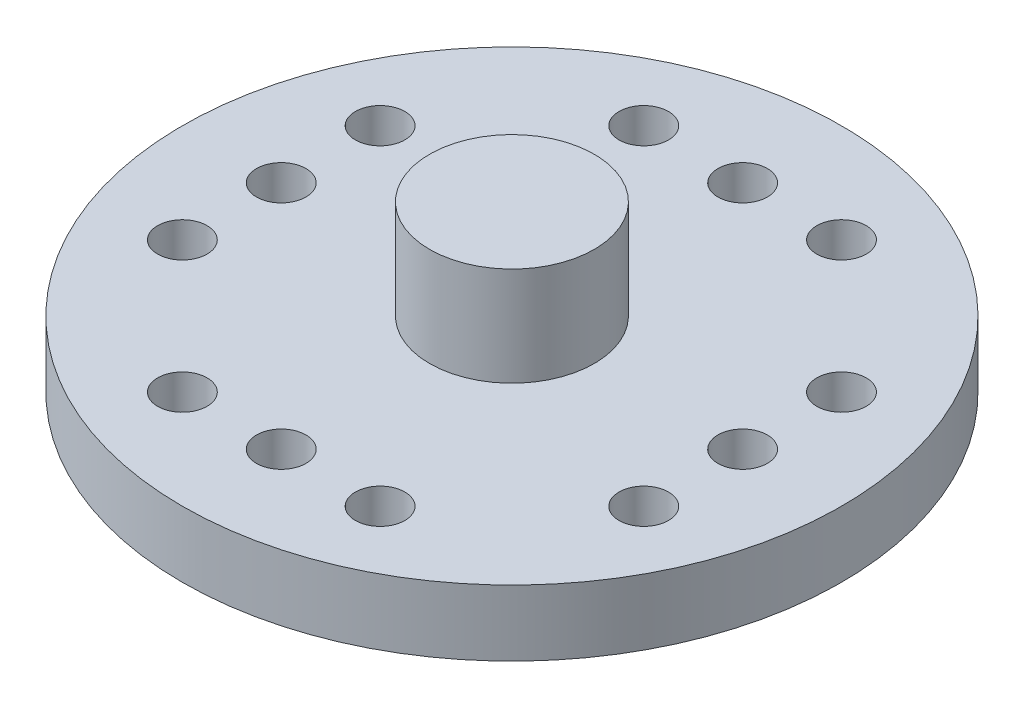
SolidWorks part; units mm, degrees
ref_plane "前视基准面" through (0, 0, 0) normal (0, 0, 1) x (1, 0, 0)
ref_plane "上视基准面" through (0, 0, 0) normal (0, 1, 0) x (1, 0, 0)
ref_plane "右视基准面" through (0, 0, 0) normal (1, 0, 0) x (0, 0, -1)
sketch "草图1" plane through (0, 0, 0) normal (0, 1, 0) x (1, 0, 0)
  circle A0 centre (0, 0) radius 10
  dimension "D1" = 20
extrude "凸台-拉伸1" add sketch "草图1" along normal blind 2
sketch "草图2" plane through (0, 2, 0) normal (0, 1, 0) x (1, 0, 0)
  circle A0 centre (0, 0) radius 2.5
  dimension "D1" = 5
extrude "凸台-拉伸2" add sketch "草图2" along normal blind 3
sketch "草图3" plane through (0, 2, 0) normal (0, 1, 0) x (1, 0, 0)
  line L0 (-8.4636, 7) -> (12.1943, 7) construction
  line L1 (0, -11.1503) -> (0, 10.1759) construction
  circle A0 centre (0, 0) radius 7 construction
  circle A1 centre (0, 7) radius 0.75
  circle A2 centre (-3, 7) radius 0.75
  circle A3 centre (3, 7) radius 0.75
  circle A4 centre (7, 3) radius 0.75
  circle A5 centre (7, 0) radius 0.75
  circle A6 centre (7, -3) radius 0.75
  circle A7 centre (3, -7) radius 0.75
  circle A8 centre (0, -7) radius 0.75
  circle A9 centre (-3, -7) radius 0.75
  circle A10 centre (-7, -3) radius 0.75
  circle A11 centre (-7, 0) radius 0.75
  circle A12 centre (-7, 3) radius 0.75
  point P34 (0, 0)
  dimension "D1" = 14
  dimension "D2" = 1.5
  dimension "D3" = 1.5
  dimension "D4" = 1.5
  dimension "D5" = 3
  dimension "D6" = 3
  dimension "D7" = 4
extrude "切除-拉伸1" cut sketch "草图3" against normal through all contours A0 A12 | A2 | A1 | A3 | A4 | A5 | A6 | A7 | A9 | A10 | A11 | A8
